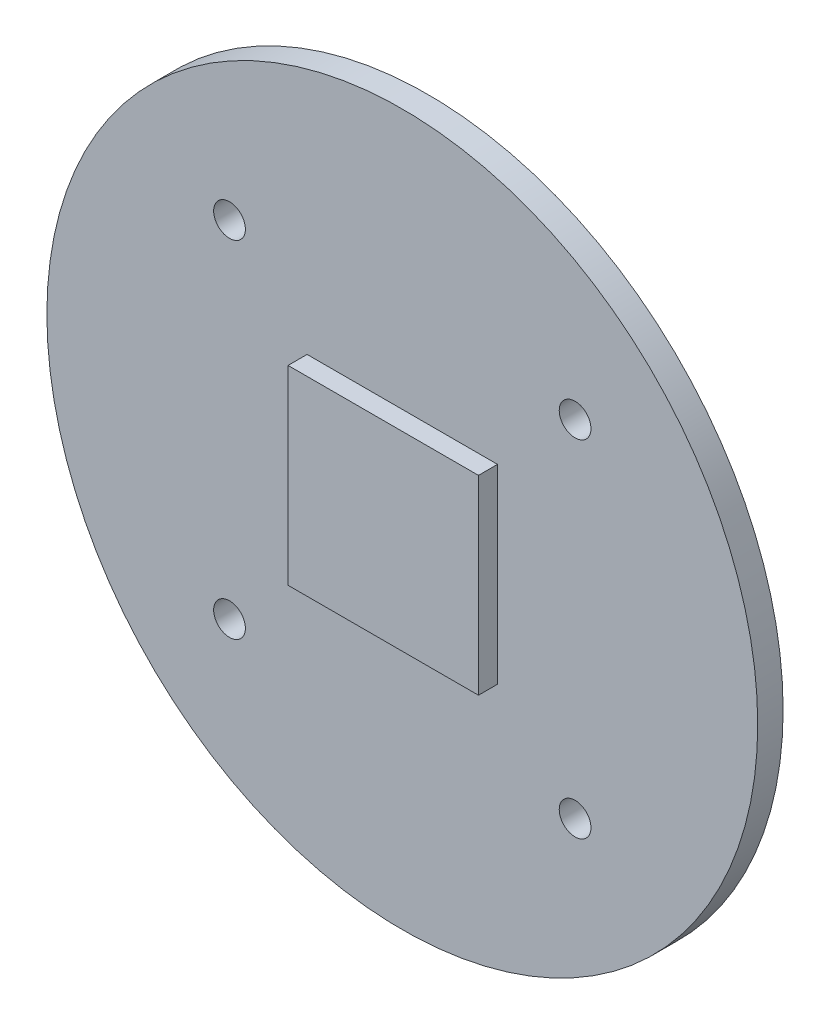
SolidWorks part; units mm, degrees
ref_plane "前视基准面" through (0, 0, 0) normal (0, 0, 1) x (1, 0, 0)
ref_plane "上视基准面" through (0, 0, 0) normal (0, 1, 0) x (1, 0, 0)
ref_plane "右视基准面" through (0, 0, 0) normal (1, 0, 0) x (0, 0, -1)
sketch "草图1" plane through (0, 0, 0) normal (0, 0, 1) x (1, 0, 0)
  circle A0 centre (0, 0) radius 28
  dimension "D1" = 56
extrude "凸台-拉伸1" add sketch "草图1" along normal blind 2
sketch "草图2" plane through (0, 0, 2) normal (0, 0, 1) x (1, 0, 0)
  line L1 (-7.5, -7.5) -> (7.5, -7.5)
  line L2 (-7.5, -7.5) -> (-7.5, 7.5)
  line L3 (-7.5, 7.5) -> (7.5, 7.5)
  line L4 (7.5, -7.5) -> (7.5, 7.5)
  line L5 (-7.5, -7.5) -> (7.5, 7.5) construction
  line L6 (-7.5, 7.5) -> (7.5, -7.5) construction
  point P0 (0, 0)
  dimension "D1" = 15
extrude "凸台-拉伸2" add sketch "草图2" along normal blind 1.5
sketch "草图4" plane through (0, 0, 0) normal (0, 0, -1) x (-1, 0, 0)
  line L1 (14, -10) -> (24, -10)
  line L2 (14, -10) -> (14, 10)
  line L3 (14, 10) -> (24, 10)
  line L4 (24, -10) -> (24, 10)
  line L5 (14, -10) -> (24, 10) construction
  line L6 (14, 10) -> (24, -10) construction
  point P0 (19, 0)
  dimension "D1" = 20
  dimension "D2" = 10
extrude "凸台-拉伸3" add sketch "草图4" along normal blind 1.5
sketch "草图5" plane through (0, 0, 0) normal (0, 0, -1) x (-1, 0, 0)
  line L1 (-7.5, -7.5) -> (7.5, -7.5)
  line L2 (-7.5, -7.5) -> (-7.5, 7.5)
  line L3 (-7.5, 7.5) -> (7.5, 7.5)
  line L4 (7.5, -7.5) -> (7.5, 7.5)
  line L5 (-7.5, -7.5) -> (7.5, 7.5) construction
  line L6 (-7.5, 7.5) -> (7.5, -7.5) construction
  point P0 (0, 0)
  dimension "D1" = 15
extrude "凸台-拉伸4" add sketch "草图5" along normal blind 1.5
sketch "草图6" plane through (0, 0, 0) normal (0, 0, -1) x (-1, 0, 0)
  line L0 (0, 0) -> (19.799, 19.799)
  line L1 (0, 0) -> (19.799, -19.799)
  line L2 (0, 0) -> (14, 0)
  line L3 (14, 10) -> (14, -10) construction
  line L4 (0, 0) -> (-19.799, -19.799)
  line L5 (0, 0) -> (-19.799, 19.799)
  circle A0 centre (0, 0) radius 28 construction
  circle A1 centre (13.6118, 13.6118) radius 1.25
  circle A2 centre (13.6118, -13.6118) radius 1.25
  circle A3 centre (-13.6118, -13.6118) radius 1.25
  circle A4 centre (-13.6118, 13.6118) radius 1.25
  point P1 (13.6118, 13.6118)
  point P15 (-13.6118, 13.6118)
  point P16 (-13.6118, -13.6118)
  point P17 (13.6118, -13.6118)
  point P18 (0, 0)
  point P27 (0, 0)
  dimension "D4" = 2.5
  dimension "D1" = 45
  dimension "D2" = 19.25
  dimension "D3" = 4
  dimension "D5" = 4
extrude "切除-拉伸1" cut sketch "草图6" against normal blind 10 contours L5 A4 | L5 A4 | L4 A3 | L4 A3 | L1 A2 | L1 A2 | L0 A1 | L0 A1
